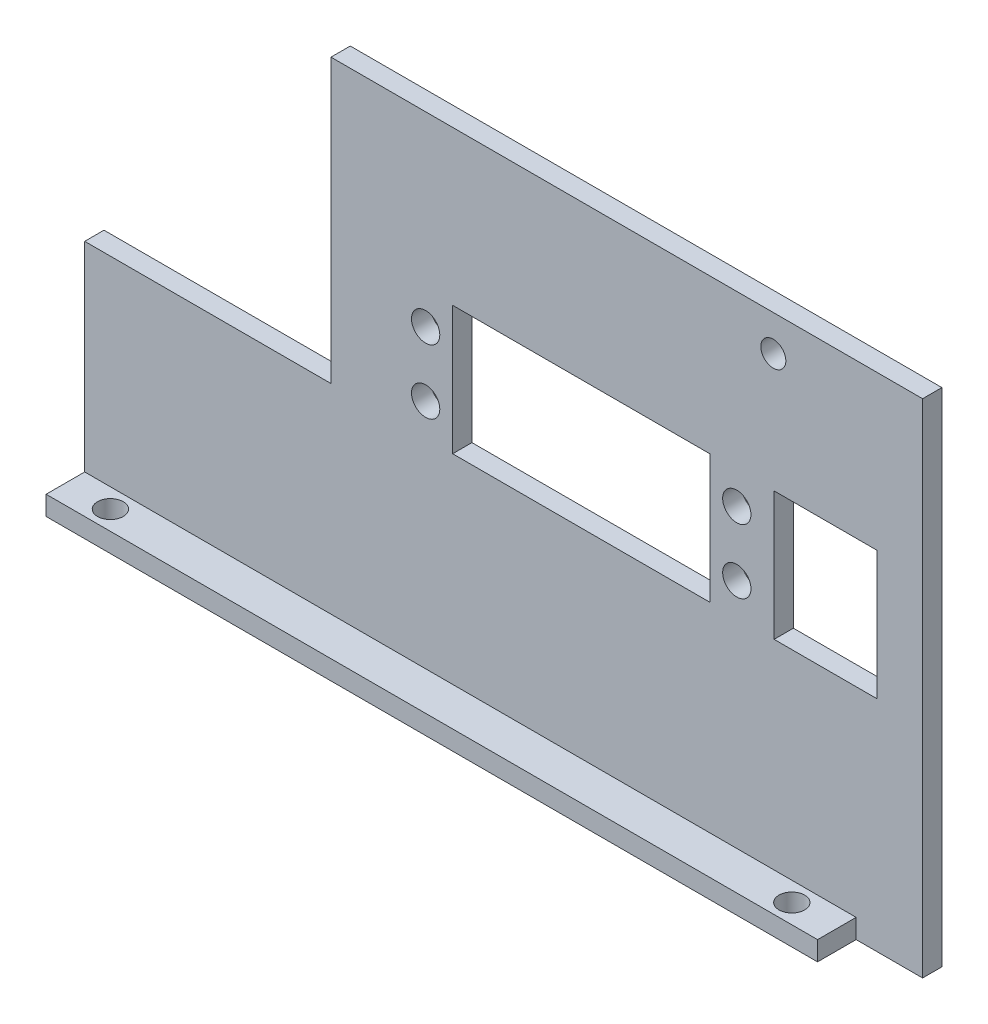
SolidWorks part; units mm, degrees
ref_plane "前视基准面" through (0, 0, 0) normal (0, 0, 1) x (1, 0, 0)
ref_plane "上视基准面" through (0, 0, 0) normal (0, 1, 0) x (1, 0, 0)
ref_plane "右视基准面" through (0, 0, 0) normal (1, 0, 0) x (0, 0, -1)
sketch "草图1" plane through (0, 0, 0) normal (0, 0, 1) x (1, 0, 0)
  line L0 (18.8415, 8.7222) -> (18.8415, -11.2778)
  line L1 (-0.0842, 32.6887) -> (91.9436, 32.6887)
  line L2 (-38.3963, -11.2778) -> (-38.3963, -45.3491)
  line L3 (-38.3963, -45.3491) -> (91.9436, -45.3491)
  line L4 (91.9436, 32.6887) -> (91.9436, -45.3491)
  line L5 (58.8415, 8.7222) -> (58.8415, -11.2778)
  line L6 (18.8415, 8.7222) -> (58.8415, 8.7222)
  line L7 (18.8415, -11.2778) -> (58.8415, -11.2778)
  line L8 (-0.0842, 8.7222) -> (-0.0842, 32.6887)
  line L10 (-0.0842, 8.7222) -> (-0.0842, -11.2778)
  line L11 (-0.0842, -11.2778) -> (-17.0842, -11.2778)
  line L13 (68.8415, -11.2778) -> (84.8415, -11.2778)
  line L14 (68.8415, -11.2778) -> (68.8415, 8.7222)
  line L15 (68.8415, 8.7222) -> (84.8415, 8.7222)
  line L16 (84.8415, -11.2778) -> (84.8415, 8.7222)
  line L17 (-17.0842, -11.2778) -> (-38.3963, -11.2778)
  circle A3 centre (14.6415, 3.7222) radius 2.2
  circle A4 centre (14.6415, -6.2778) radius 2.2
  circle A5 centre (63.0415, 3.7222) radius 2.2
  circle A6 centre (63.0415, -6.2778) radius 2.2
  circle A7 centre (68.7195, 27.1397) radius 1.95
  dimension "D3" = 10
  dimension "D2" = 17
  dimension "D4" = 16
  dimension "D5" = 48.4
  dimension "D6" = 48.4
  dimension "D10" = 40
extrude "凸台-拉伸1" add sketch "草图1" along normal mid plane 3
sketch "草图2" plane through (0, 0, 1.5) normal (0, 0, 1) x (1, 0, 0)
  line L0 (-38.3963, -45.3491) -> (81.6037, -45.3491)
  line L1 (-38.3963, -45.3491) -> (91.9436, -45.3491) construction
  line L2 (81.6037, -45.3491) -> (81.6037, -42.3491)
  line L3 (81.6037, -42.3491) -> (-38.3963, -42.3491)
  line L4 (-38.3963, -11.2778) -> (-38.3963, -45.3491) construction
  line L5 (-38.3963, -42.3491) -> (-38.3963, -45.3491)
  dimension "D1" = 120
  dimension "D2" = 3
extrude "凸台-拉伸2" add sketch "草图2" along normal blind 6
sketch "草图3" plane through (0, -42.3491, 0) normal (0, 1, 0) x (1, 0, 0)
  line L0 (-38.3963, -7.5) -> (-38.3963, -1.5) construction
  circle A0 centre (-31.3963, -4.5) radius 2
  circle A1 centre (74.6037, -4.5) radius 2
  point P6 (-38.3963, -4.5)
  dimension "D1" = 7
  dimension "D2" = 113
extrude "切除-拉伸1" cut sketch "草图3" against normal blind 6
